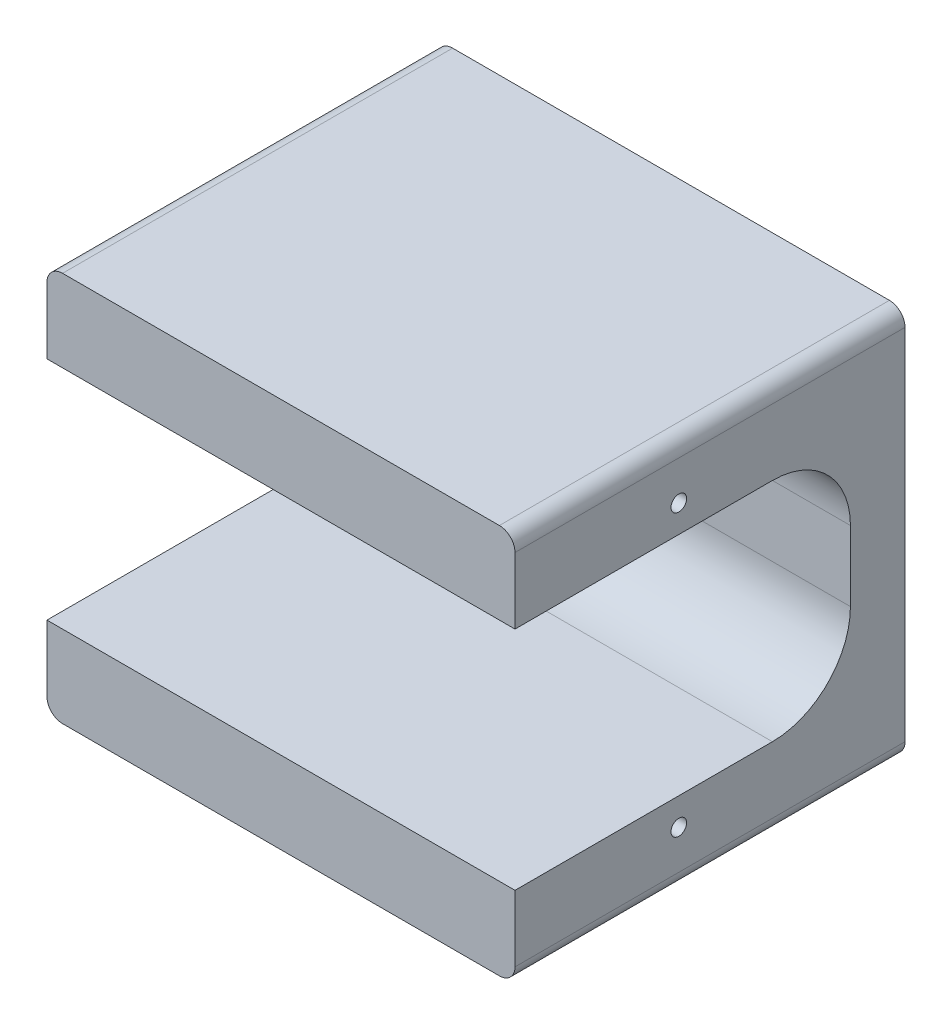
SolidWorks part; units mm, degrees
ref_plane "Plano frontal" through (0, 0, 0) normal (0, 0, 1) x (1, 0, 0)
ref_plane "Plano superior" through (0, 0, 0) normal (0, 1, 0) x (1, 0, 0)
ref_plane "Plano direito" through (0, 0, 0) normal (1, 0, 0) x (0, 0, -1)
sketch "Esboço1" plane through (0, 0, 0) normal (0, 0, 1) x (1, 0, 0)
  line L1 (-30, -25) -> (30, -25)
  line L2 (-30, -25) -> (-30, 25)
  line L3 (-30, 25) -> (30, 25)
  line L4 (30, -25) -> (30, 25)
  line L5 (-30, -25) -> (30, 25) construction
  line L6 (-30, 25) -> (30, -25) construction
  point P0 (0, 0)
  dimension "D1" = 50
  dimension "D2" = 60
extrude "Ressalto-extrusão1" add sketch "Esboço1" along normal blind 50
sketch "Esboço2" plane through (0, 0, 50) normal (0, 0, 1) x (1, 0, 0)
  line L0 (30, -25) -> (30, 25) construction
  line L1 (-30, -14.5) -> (30, -14.5)
  line L2 (-30, -14.5) -> (-30, 14.5)
  line L3 (-30, 14.5) -> (30, 14.5)
  line L4 (30, -14.5) -> (30, 14.5)
  line L5 (-30, -14.5) -> (30, 14.5) construction
  line L6 (-30, 14.5) -> (30, -14.5) construction
  point P0 (0, 0)
  dimension "D1" = 29
extrude "Corte-extrusão1" cut sketch "Esboço2" against normal blind 43
fillet "Filete1" radius 10 2 edges at (0, -14.5, 7) (0, 14.5, 7)
fillet "Filete2" radius 2 4 edges at (-30, -25, 25) (30, -25, 25) (-30, 25, 25) (30, 25, 25)
sketch "Esboço3" plane through (30, 0, 0) normal (1, 0, 0) x (0, 0, -1)
  line L0 (0, -23) -> (0, 23) construction
  line L1 (0, 0) -> (-25.4273, 0) construction
  circle A0 centre (-29, -18) radius 1
  circle A1 centre (-29, 18) radius 1
  dimension "D1" = 2
  dimension "D2" = 29
  dimension "D3" = 36
extrude "Corte-extrusão2" cut sketch "Esboço3" against normal blind 10
ref_plane "Plano1" through (0, 0, 0) normal (-1, 0, 0) x (0, 0, 1)
mirror "Espelhar1" about plane through (0, 0, 0) normal (-1, 0, 0) of "Corte-extrusão2"
